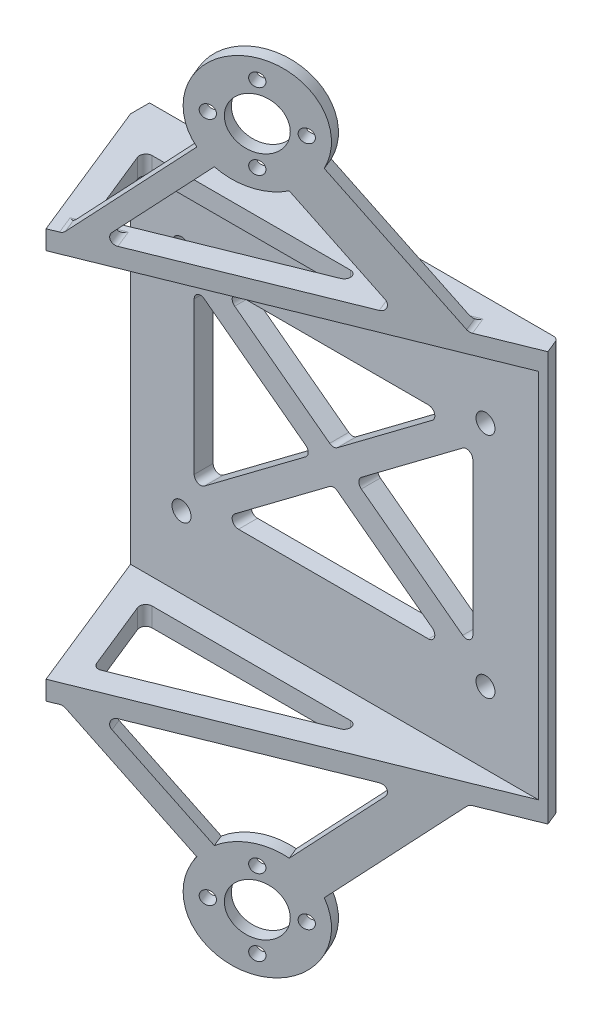
SolidWorks part; units mm, degrees
ref_plane "前视基准面" through (0, 0, 0) normal (0, 0, 1) x (1, 0, 0)
ref_plane "上视基准面" through (0, 0, 0) normal (0, 1, 0) x (1, 0, 0)
ref_plane "右视基准面" through (0, 0, 0) normal (1, 0, 0) x (0, 0, -1)
sketch "草图2" plane through (0, 0, 0) normal (0, 0, 1) x (1, 0, 0)
  line L5 (32.393, -32.3198) -> (-32.0526, -32.3198)
  line L6 (32.393, -32.3198) -> (32.393, 32.283)
  line L7 (32.393, 32.283) -> (-32.0526, 32.283)
  line L8 (-32.0526, -32.3198) -> (-32.0526, 32.283)
sketch "草图3" plane through (0, 0, 0) normal (0, 0, 1) x (1, 0, 0)
  circle A0 centre (24, -18) radius 1.5
  circle A1 centre (-24, -18) radius 1.5
  circle A2 centre (-24, 18) radius 1.5
  circle A3 centre (24, 18) radius 1.5
  dimension "D1" = 3
  dimension "D2" = 3
  dimension "D3" = 3
  dimension "D4" = 3
extrude "凸台-拉伸2" add sketch "草图2" along normal blind 3
extrude "切除-拉伸1" cut sketch "草图3" along normal blind 4
sketch "草图9" plane through (0, 32.283, 0) normal (0, 1, 0) x (1, 0, 0)
  line L1 (-32.0526, -3) -> (32.393, -3)
  line L5 (-32.0526, -3) -> (-23.0089, -25.3838)
  line L6 (-23.0089, -25.3838) -> (32.393, -3)
  line L7 (-20.7986, -20.1767) -> (11.8148, -7)
  line L8 (-26.1223, -7) -> (11.8148, -7)
  line L9 (-26.1223, -7) -> (-20.7986, -20.1767)
  dimension "D1" = 22
  dimension "D2" = 4
extrude "凸台-拉伸3" add sketch "草图9" against normal blind 3
sketch "草图10" plane through (0, -32.3198, 0) normal (0, -1, 0) x (1, 0, 0)
  line L0 (-23.0089, 25.3838) -> (-32.0526, 3)
  line L1 (-32.0526, 3) -> (32.393, 3)
  line L2 (32.393, 3) -> (-23.0089, 25.3838)
  line L4 (25.5, 3) -> (22.5, 3) construction
  line L5 (-23.0089, 25.3838) -> (32.393, 3) construction
  line L6 (11.8148, 7) -> (-20.7986, 20.1767)
  line L7 (-20.7986, 20.1767) -> (-26.1223, 7)
  line L8 (-26.1223, 7) -> (11.8148, 7)
  line L10 (-32.0526, 0) -> (32.393, 0) construction
  dimension "D1" = 4
extrude "凸台-拉伸4" add sketch "草图10" against normal blind 3
sketch "草图13" plane through (0, 32.283, 0) normal (0, 1, 0) x (1, 0, 0)
  line L0 (32.393, -3) -> (33.435, -2.579)
  line L1 (33.435, -2.579) -> (32.393, 0)
  line L2 (-23.0089, -25.3838) -> (32.393, -3) construction
  line L3 (32.393, -3) -> (32.393, 0)
  dimension "D1" = 2.7816
extrude "凸台-拉伸6" add sketch "草图13" against normal up to surface (64.6028 mm away) contours L3 L1 L0 up to face at (-4.4656, -32.3198, 6.2768)
sketch "草图11" plane through (5.5877, 0, 13.8301) normal (0.3746, 0, 0.9272) x (0.9272, 0, -0.3746)
  line L0 (-5.2157, 59.7316) -> (-5.2157, 47.7316) construction
  line L1 (0.7843, 53.7316) -> (-11.2157, 53.7316) construction
  line L2 (-5.2157, -47.7684) -> (-5.2157, -59.7684) construction
  line L3 (0.7843, -53.7684) -> (-11.2157, -53.7684) construction
  line L4 (-30.8425, -0.0184) -> (30.0343, -0.0184) construction
  line L5 (11.9902, 32.283) -> (-1.337, 45.6103)
  line L7 (-0.966, 29.283) -> (-0.966, -29.3198) construction
  line L8 (28.9105, 29.283) -> (-30.8425, 29.283) construction
  line L9 (28.9105, -29.3198) -> (-30.8425, -29.3198) construction
  line L11 (-5.2157, 53.7316) -> (-5.2157, -53.7684) construction
  line L12 (-5.2157, 53.7316) -> (16.2329, 32.283) construction
  line L13 (16.2329, -32.3198) -> (-5.2157, -53.7684) construction
  line L14 (0.7843, 53.7316) -> (-5.2157, 47.7316) construction
  line L15 (-11.2157, 53.7316) -> (-5.2157, 47.7316) construction
  line L16 (-11.2157, -53.7684) -> (-5.2157, -47.7684) construction
  line L17 (-5.2157, -53.7684) -> (-58.9657, -0.0184) construction
  line L18 (-58.9657, -0.0184) -> (-5.2157, 53.7316) construction
  line L19 (-12.5513, 48.5173) -> (-28.7856, 32.283)
  line L20 (2.9056, -49.8897) -> (20.4755, -32.3198)
  line L21 (-1.337, -45.6471) -> (11.9902, -32.3198)
  line L22 (20.4755, 32.283) -> (2.9056, 49.8529)
  line L24 (-24.543, 32.283) -> (-10.43, 46.396)
  line L25 (-24.543, -32.3198) -> (-10.43, -46.4328)
  line L26 (-28.7856, -32.3198) -> (-12.5513, -48.5541)
  line L27 (30.0343, -32.3198) -> (-30.8425, -32.3198) construction
  line L28 (-30.8425, 32.283) -> (30.0343, 32.283) construction
  line L29 (-28.7856, -32.3198) -> (-24.543, -32.3198)
  line L30 (-24.543, 32.283) -> (-28.7856, 32.283)
  line L32 (20.4755, -32.3198) -> (11.9902, -32.3198)
  line L34 (20.4755, 32.283) -> (11.9902, 32.283)
  line L35 (30.0343, -32.3198) -> (30.0343, 32.283) construction
  line L36 (-30.8425, 29.283) -> (-30.8425, -29.3198) construction
  circle A0 centre (-5.2157, 53.7316) radius 6 construction
  circle A1 centre (-11.2157, 53.7316) radius 1.05
  circle A2 centre (-5.2157, 53.7316) radius 4
  circle A3 centre (-5.2157, 59.7316) radius 1.05
  circle A4 centre (0.7843, 53.7316) radius 1.05
  circle A5 centre (-5.2157, 47.7316) radius 1.05
  circle A6 centre (-5.2157, 53.7316) radius 9
  circle A7 centre (-5.2157, -53.7684) radius 6 construction
  circle A8 centre (-11.2157, -53.7684) radius 1.05
  circle A9 centre (-5.2157, -53.7684) radius 4
  circle A10 centre (-5.2157, -47.7684) radius 1.05
  circle A11 centre (0.7843, -53.7684) radius 1.05
  circle A12 centre (-5.2157, -59.7684) radius 1.05
  circle A13 centre (-5.2157, -53.7684) radius 9
  point P41 (-0.4041, -0.0184)
  dimension "D1" = 2.1
  dimension "D2" = 2.1
  dimension "D3" = 2.1
  dimension "D4" = 2.1
  dimension "D5" = 18
  dimension "D6" = 12
  dimension "D7" = 8
  dimension "D8" = 2.1
  dimension "D9" = 2.1
  dimension "D10" = 2.1
  dimension "D11" = 2.1
  dimension "D12" = 18
  dimension "D13" = 12
  dimension "D14" = 8
  dimension "D18" = 107.5
  dimension "D25" = 6
  dimension "D26" = 1.5
  dimension "D27" = 1.5
  dimension "D28" = 1.5
  dimension "D29" = 1.5
extrude "凸台-拉伸7" add sketch "草图11" against normal blind 2
fillet "圆角1" radius 1 1 edges at (32.393, -0.0184, 0)
fillet "圆角2" radius 1 12 edges at (-17.5428, 32.283, 22.0968) (-21.4765, 32.283, 23.6862) (-19.8842, 32.283, 21.9643) (24.1977, 32.283, 5.2326) (19.8894, 32.283, 5.8947) (-17.5428, -32.3198, 22.0968) (16.3303, -32.3198, 8.4112) (-21.4765, -32.3198, 23.6862) (-19.8842, -32.3198, 21.9643) (19.8894, -32.3198, 5.8947) (24.1977, -32.3198, 5.2326) (16.3303, 32.283, 8.4112)
fillet "圆角3" radius 1 6 edges at (-26.1223, -30.8198, 7) (-20.7986, -30.8198, 20.1767) (-26.1223, 30.783, 7) (-20.7986, 30.783, 20.1767) (11.8148, 30.783, 7) (11.8148, -30.8198, 7)
sketch "草图15" plane through (0, 0, 3) normal (0, 0, 1) x (1, 0, 0)
  line L0 (-24, 18) -> (-24, -18) construction
  line L1 (24, 18) -> (24, -18) construction
  line L2 (24, -18) -> (-24, -18) construction
  line L3 (-24, 18) -> (24, 18) construction
  line L4 (24, 18) -> (-24, -18) construction
  line L5 (-24, 18) -> (24, -18) construction
  line L6 (-18, 16) -> (18, 16)
  line L7 (18, 16) -> (0, 2.5)
  line L8 (0, 2.5) -> (-18, 16)
  line L9 (-22, 14) -> (-3.3333, 0)
  line L10 (-3.3333, 0) -> (-22, -14)
  line L11 (-22, -14) -> (-22, 14)
  line L12 (-18, -16) -> (18, -16)
  line L13 (18, -16) -> (0, -2.5)
  line L14 (0, -2.5) -> (-18, -16)
  line L16 (22, 14) -> (3.3333, 0)
  line L17 (3.3333, 0) -> (22, -14)
  line L18 (22, -14) -> (22, 14)
  dimension "D1" = 2
  dimension "D2" = 2
  dimension "D3" = 2
  dimension "D4" = 2
  dimension "D5" = 2
  dimension "D6" = 2
  dimension "D7" = 2
  dimension "D8" = 2
  dimension "D9" = 2
  dimension "D10" = 2
extrude "切除-拉伸3" cut sketch "草图15" against normal through all
fillet "圆角5" radius 1 12 edges at (-18, -16, 1.5) (18, -16, 1.5) (22, -14, 1.5) (22, 14, 1.5) (-3.3333, 0, 1.5) (-22, -14, 1.5) (0, 2.5, 1.5) (3.3333, 0, 1.5) (-18, 16, 1.5) (0, -2.5, 1.5) (-22, 14, 1.5) (18, 16, 1.5)
